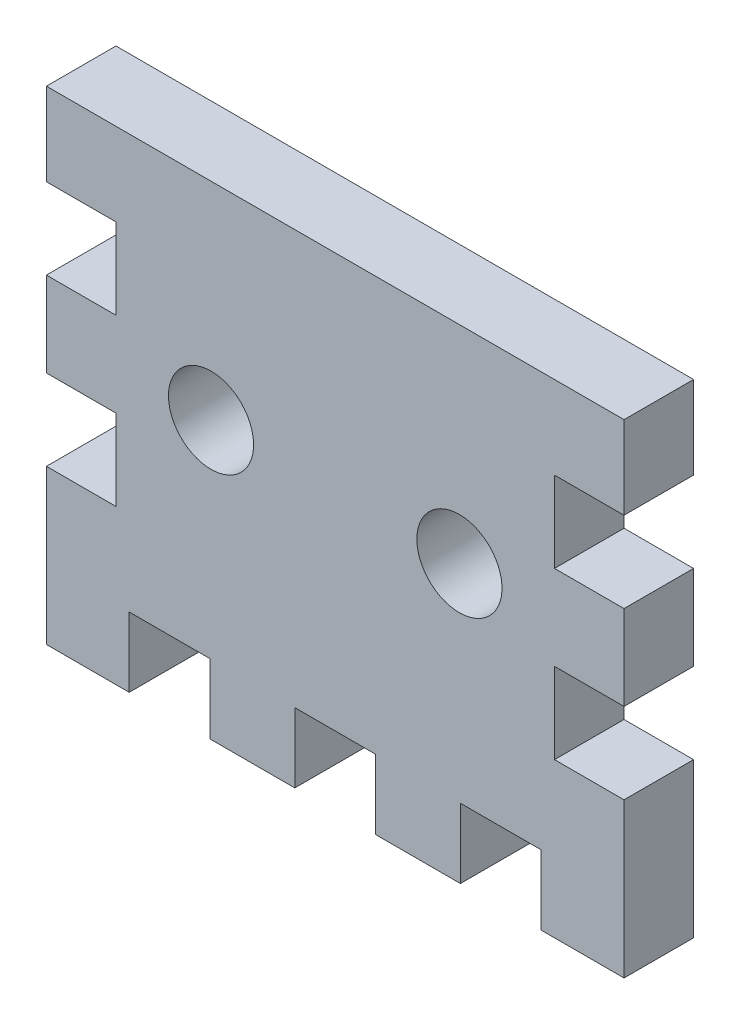
SolidWorks part; units mm, degrees
material "Mahogany"
ref_plane "Front Plane" through (0, 0, 0) normal (0, 0, 1) x (1, 0, 0)
ref_plane "Top Plane" through (0, 0, 0) normal (0, 1, 0) x (1, 0, 0)
ref_plane "Right Plane" through (0, 0, 0) normal (1, 0, 0) x (0, 0, -1)
sketch "Sketch1" plane through (0, 0, 0) normal (0, 0, 1) x (1, 0, 0)
  line L1 (27.94, -5.334) -> (72.2376, -5.334)
  line L2 (27.94, -5.334) -> (27.94, 31.75)
  line L3 (27.94, 31.75) -> (72.2376, 31.75)
  line L4 (72.2376, -5.334) -> (72.2376, 31.75)
  line L5 (72.2376, 0) -> (72.2376, -5.334) construction
  line L6 (27.94, -5.334) -> (34.1376, -5.334) construction
  line L7 (27.94, -5.334) -> (27.94, 0) construction
  dimension "D1" = 37.084
extrude "Boss-Extrude1" add sketch "Sketch1" against normal blind 5.334 contours L2 L3 L4 L1
sketch "Sketch2" plane through (0, 0, 0) normal (0, 0, 1) x (1, 0, 0)
  line L1 (65.8876, -5.334) -> (59.69, -5.334)
  line L2 (65.8876, -5.334) -> (65.8876, 0)
  line L3 (65.8876, 0) -> (59.69, 0)
  line L4 (59.69, -5.334) -> (59.69, 0)
  line L6 (27.94, -5.334) -> (72.2376, -5.334) construction
  line L7 (72.2376, -5.334) -> (72.2376, 31.75) construction
  dimension "D1" = 6.35
  dimension "D2" = 6.1976
  dimension "D3" = 5.334
extrude "Cut-Extrude1" cut sketch "Sketch2" against normal through all
pattern_linear "LPattern1" count 3 spacing 12.7 along (-1, 0, 0) of "Cut-Extrude1"
sketch "Sketch3" plane through (0, 0, -5.334) normal (0, 0, -1) x (-1, 0, 0)
  line L0 (-53.1876, 0) -> (-46.99, 0) construction
  line L1 (-50.0888, 31.75) -> (-50.0888, 0) construction
  line L4 (-72.2376, -5.334) -> (-72.2376, 31.75) construction
  line L5 (-72.2376, 6.5024) -> (-66.9036, 6.5024)
  line L6 (-72.2376, 6.5024) -> (-72.2376, 12.7)
  line L7 (-72.2376, 12.7) -> (-66.9036, 12.7)
  line L8 (-66.9036, 6.5024) -> (-66.9036, 12.7)
  line L9 (-27.94, 6.5024) -> (-27.94, 12.7)
  line L10 (-27.94, 6.5024) -> (-33.274, 6.5024)
  line L11 (-33.274, 6.5024) -> (-33.274, 12.7)
  line L12 (-27.94, 12.7) -> (-33.274, 12.7)
  line L13 (-72.2376, 0) -> (-3.0923, 0) construction
  line L15 (-27.94, 31.75) -> (-72.2376, 31.75) construction
  dimension "D1" = 6.5024
  dimension "D2" = 6.1976
  dimension "D3" = 5.334
extrude "Cut-Extrude2" cut sketch "Sketch3" against normal through all
pattern_linear "LPattern2" count 2 spacing 12.7 along (0, 1, 0) of "Cut-Extrude2"
sketch "Sketch4" plane through (0, 0, -5.334) normal (0, 0, -1) x (-1, 0, 0)
  line L0 (-50.0888, 31.75) -> (-50.0888, 0) construction
  line L1 (-27.94, 31.75) -> (-72.2376, 31.75) construction
  line L2 (-53.1876, 0) -> (-46.99, 0) construction
  line L3 (-59.6138, 15.875) -> (-40.5638, 15.875) construction
  point P8 (-50.0888, 15.875)
  point P9 (-50.0888, 15.875)
  dimension "D1" = 19.05
hole_wizard "F (0.257) Diameter Hole1" positions "Sketch6" profile "Sketch5" hole size "F" standard "ANSI Inch" end condition through all
sketch "Sketch6" plane through (0, 0, -5.334) normal (0, 0, -1) x (-1, 0, 0)
  point P0 (-59.6138, 15.875)
  point P3 (-40.5638, 15.875)
sketch "Sketch5" plane through (59.6138, 15.875, -5.334) normal (1, 0, 0) x (0, 1, 0)
  line L0 (0, 0) -> (0, 5.334)
  line L1 (0, 5.334) -> (3.2639, 5.334)
  line L2 (3.2639, 5.334) -> (3.2639, 0)
  line L5 (3.2639, 0) -> (0, 0)
  line L11 (0, -6.35) -> (0, 107.95) construction
  dimension "Thru Hole Dia." = 6.5278
  dimension "Thru Hole Depth" = 5.334
